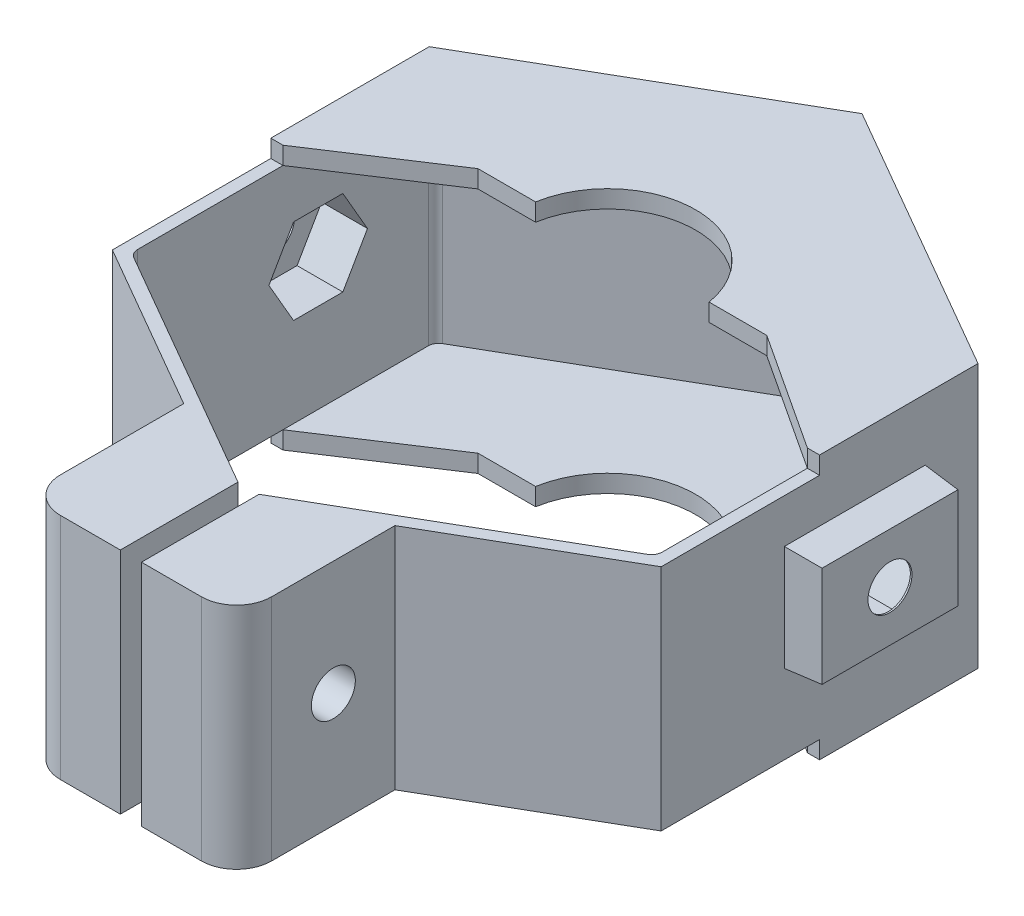
SolidWorks part; units mm, degrees
other "Markup1"
sketch "Sketch10" plane through (-23.4372, 15.24, -10.2057) normal (0, 1, 0) x (1, 0, 0)
ref_plane "Front Plane" through (0, 0, 0) normal (0, 0, 1) x (1, 0, 0)
ref_plane "Top Plane" through (0, 0, 0) normal (0, 1, 0) x (1, 0, 0)
ref_plane "Right Plane" through (0, 0, 0) normal (1, 0, 0) x (0, 0, -1)
sketch "Sketch1" plane through (0, 0, 0) normal (0, 1, 0) x (1, 0, 0)
  line L0 (-7.62, -31.1149) -> (-7.62, -40.0049)
  line L1 (0, 10.2057) -> (-19.7973, -1.2243)
  line L2 (-19.7973, -1.2243) -> (-19.7973, -24.0843)
  line L3 (-19.7973, -24.0843) -> (-7.62, -31.1149)
  line L4 (7.62, -31.1149) -> (19.7973, -24.0843)
  line L5 (19.7973, -24.0843) -> (19.7973, -1.2243)
  line L6 (19.7973, -1.2243) -> (0, 10.2057)
  line L7 (0, 9.1897) -> (-18.9175, -1.7323)
  line L8 (-18.9175, -1.7323) -> (-18.9175, -23.5763)
  line L9 (-18.9175, -23.5763) -> (0, -34.4983)
  line L10 (0, -34.4983) -> (18.9175, -23.5763)
  line L11 (18.9175, -23.5763) -> (18.9175, -1.7323)
  line L12 (18.9175, -1.7323) -> (0, 9.1897)
  line L13 (-5.08, -42.5449) -> (5.08, -42.5449)
  line L14 (7.62, -31.1149) -> (7.62, -40.0049)
  circle A0 centre (0, -12.6543) radius 19.7973 construction
  circle A1 centre (0, -12.6543) radius 18.9175 construction
  arc A2 (5.08, -42.5449) -> (7.62, -40.0049) centre (5.08, -40.0049) ccw
  arc A3 (-7.62, -40.0049) -> (-5.08, -42.5449) centre (-5.08, -40.0049) ccw
  point P9 (18.9175, -12.6543)
  point P17 (19.7973, -12.6543)
  point P25 (0, -42.5449)
  dimension "D3" = 2.54
  dimension "D1" = 22.86
  dimension "D4" = 10.2057
  dimension "D5" = 10.16
  dimension "D6" = 8.89
  dimension ".68" = 21.844
extrude "Boss-Extrude1" add sketch "Sketch1" along normal blind 16.51
sketch "Sketch2" plane through (0, 16.51, 0) normal (0, 1, 0) x (1, 0, 0)
  line L0 (-0.762, -34.0583) -> (-0.762, -42.5449)
  line L1 (-18.9175, -23.5763) -> (0, -34.4983) construction
  line L2 (-5.08, -42.5449) -> (5.08, -42.5449) construction
  line L3 (0.762, -34.0583) -> (0.762, -42.5449)
  line L4 (0, -34.4983) -> (18.9175, -23.5763) construction
  line L5 (-0.762, -34.0583) -> (0, -34.4983)
  line L6 (0, -34.4983) -> (0.762, -34.0583)
  line L7 (-0.762, -42.5449) -> (0.762, -42.5449)
  dimension "D1" = 1.524
extrude "Cut-Extrude1" cut sketch "Sketch2" against normal through all
sketch "Sketch4" plane through (-7.62, 0, 0) normal (-1, 0, 0) x (0, 0, 1)
  line L0 (35.5599, 16.51) -> (35.5599, 0) construction
  line L3 (31.1149, 16.51) -> (40.0049, 16.51) construction
  line L6 (31.1149, 0) -> (40.0049, 0) construction
  line L7 (31.1149, 8.255) -> (40.0049, 8.255) construction
  line L8 (31.1149, 16.51) -> (31.1149, 0) construction
  line L9 (40.0049, 16.51) -> (40.0049, 0) construction
  circle A1 centre (35.5599, 8.255) radius 1.5875
  dimension "D1" = 3.175
extrude "Cut-Extrude2" cut sketch "Sketch4" against normal through all
sketch "Sketch8" plane through (0, 16.51, 0) normal (0, 1, 0) x (1, 0, 0)
  line L0 (-10.4194, -7.0858) -> (10.4194, -7.0858)
  line L1 (19.7973, -1.2243) -> (0, 10.2057)
  line L2 (0, 10.2057) -> (-19.7973, -1.2243)
  line L3 (-18.9175, -12.6543) -> (-10.4194, -7.0858)
  line L4 (-18.9175, -1.7323) -> (-18.9175, -23.5763) construction
  line L5 (18.9175, -12.6543) -> (10.4194, -7.0858)
  line L6 (18.9175, -23.5763) -> (18.9175, -1.7323) construction
  line L7 (19.7973, -1.2243) -> (19.7973, -12.6543)
  line L8 (19.7973, -24.0843) -> (19.7973, -1.2243) construction
  line L9 (19.7973, -12.6543) -> (18.9175, -12.6543)
  line L10 (-19.7973, -1.2243) -> (-19.7973, -12.6543)
  line L11 (-19.7973, -1.2243) -> (-19.7973, -24.0843) construction
  line L12 (-19.7973, -12.6543) -> (-18.9175, -12.6543)
  dimension "D1" = 10.16
  dimension "D2" = 20.8387
extrude "Boss-Extrude3" add sketch "Sketch8" along normal blind 1.27
sketch "Sketch9" plane through (0, 0, 0) normal (0, -1, 0) x (1, 0, 0)
  line L0 (-10.4194, 7.0858) -> (10.4194, 7.0858)
  line L1 (19.7973, 1.2243) -> (0, -10.2057)
  line L2 (0, -10.2057) -> (-19.7973, 1.2243)
  line L3 (-18.9175, 12.6543) -> (-10.4194, 7.0858)
  line L4 (-18.9175, 1.7323) -> (-18.9175, 23.5763) construction
  line L5 (-18.9175, 12.6543) -> (-19.7973, 12.6543)
  line L6 (-19.7973, 1.2243) -> (-19.7973, 24.0843) construction
  line L7 (-19.7973, 12.6543) -> (-19.7973, 1.2243)
  line L8 (10.4194, 7.0858) -> (18.9175, 12.6543)
  line L9 (18.9175, 12.6543) -> (19.7973, 12.6543)
  line L10 (19.7973, 24.0843) -> (19.7973, 1.2243) construction
  line L11 (19.7973, 12.6543) -> (19.7973, 1.2243)
extrude "Boss-Extrude4" add sketch "Sketch9" along normal blind 1.27
sketch "Sketch11" plane through (-19.7973, 0, 0) normal (-1, 0, 0) x (0, 0, 1)
  line L1 (5.0343, 5.715) -> (15.1943, 5.715)
  line L2 (5.0343, 5.715) -> (5.0343, 13.335)
  line L3 (5.0343, 13.335) -> (15.1943, 13.335)
  line L4 (15.1943, 5.715) -> (15.1943, 13.335)
  line L5 (1.2243, 17.78) -> (1.2243, -1.27) construction
  line L8 (12.6543, 16.51) -> (24.0843, 16.51) construction
  point P6 (10.1143, 13.335)
  point P9 (5.0343, 9.525)
  dimension "D1" = 8.89
  dimension "D2" = 10.16
  dimension "D3" = 7.62
  dimension "D4" = 6.985
extrude "Boss-Extrude5" add sketch "Sketch11" along normal blind 2.54 draft 4
sketch "Sketch12" plane through (-22.3373, 0, 0) normal (-1, 0, 0) x (0, 0, 1)
  line L0 (15.1943, 13.335) -> (5.0343, 13.335) construction
  line L1 (5.2119, 13.1574) -> (5.2119, 5.8926) construction
  circle A0 centre (10.1143, 9.525) radius 1.5875
  point P4 (10.1143, 13.335)
  point P7 (5.2119, 9.525)
  dimension "D1" = 3.175
extrude "Cut-Extrude3" cut sketch "Sketch12" against normal through all
sketch "Sketch13" plane through (-18.9175, 0, 0) normal (1, 0, 0) x (0, 0, -1)
  line L1 (-8.3363, 12.6046) -> (-11.8923, 12.6046)
  line L2 (-11.8923, 12.6046) -> (-13.6703, 9.525)
  line L3 (-13.6703, 9.525) -> (-11.8923, 6.4454)
  line L4 (-11.8923, 6.4454) -> (-8.3363, 6.4454)
  line L5 (-8.3363, 6.4454) -> (-6.5583, 9.525)
  line L6 (-6.5583, 9.525) -> (-8.3363, 12.6046)
  circle A0 centre (-10.1143, 9.525) radius 3.0796 construction
  point P15 (-10.1143, 12.6046)
  dimension "D1" = 3.556
extrude "Cut-Extrude4" cut sketch "Sketch13" against normal blind 3.302
mirror "Mirror1" about plane through (0, 0, 0) normal (1, 0, 0) of "Cut-Extrude4", "Boss-Extrude5"
sketch "Sketch14" plane through (22.3373, 0, 0) normal (1, 0, 0) x (0, 0, -1)
  line L0 (-15.1943, 13.335) -> (-5.0343, 13.335) construction
  line L1 (-15.0167, 5.8926) -> (-15.0167, 13.1574) construction
  circle A0 centre (-10.1143, 9.525) radius 1.5875
  point P4 (-10.1143, 13.335)
  point P7 (-15.0167, 9.525)
  dimension "D1" = 3.175
fillet "Fillet1" radius 0.762 5 edges at (18.9175, 8.255, 1.7323) (0, 8.255, -9.1897) (18.9175, 8.255, 23.5763) (-18.9175, 8.255, 23.5763) (-18.9175, 8.255, 1.7323)
extrude "Cut-Extrude6" cut sketch "Sketch14" against normal through all contours A0
sketch "Sketch15" plane through (-7.62, 0, 0) normal (-1, 0, 0) x (0, 0, 1)
  line L0 (31.1149, 16.51) -> (40.0049, 16.51) construction
  line L1 (35.5599, 11.811) -> (32.4803, 10.033)
  line L2 (32.4803, 10.033) -> (32.4803, 6.477)
  line L3 (32.4803, 6.477) -> (35.5599, 4.699)
  line L4 (35.5599, 4.699) -> (38.6395, 6.477)
  line L5 (38.6395, 6.477) -> (38.6395, 10.033)
  line L6 (38.6395, 10.033) -> (35.5599, 11.811)
  circle A0 centre (35.5599, 8.255) radius 3.0796 construction
  point P11 (35.5599, 16.51)
  dimension "D1" = 3.556
extrude "Cut-Extrude7" cut sketch "Sketch15" against normal blind 3.302
sketch "Sketch16" plane through (0, 17.78, 0) normal (0, 1, 0) x (1, 0, 0)
  line L0 (-10.4194, -7.0858) -> (10.4194, -7.0858) construction
  line L1 (-10.4194, -7.0858) -> (10.4194, -7.0858) construction
  line L2 (-6.2606, -7.0858) -> (6.2606, -7.0858)
  arc A1 (-6.2606, -7.0858) -> (6.2606, -7.0858) centre (0, -8.1475) cw
  point P3 (0, -1.7975)
  point P8 (6.2606, -7.0858)
  point P9 (-6.2606, -7.0858)
  dimension "D1" = 6.35
  dimension "D2" = 18.3532
extrude "Cut-Extrude10" cut sketch "Sketch16" against normal blind 76.2
